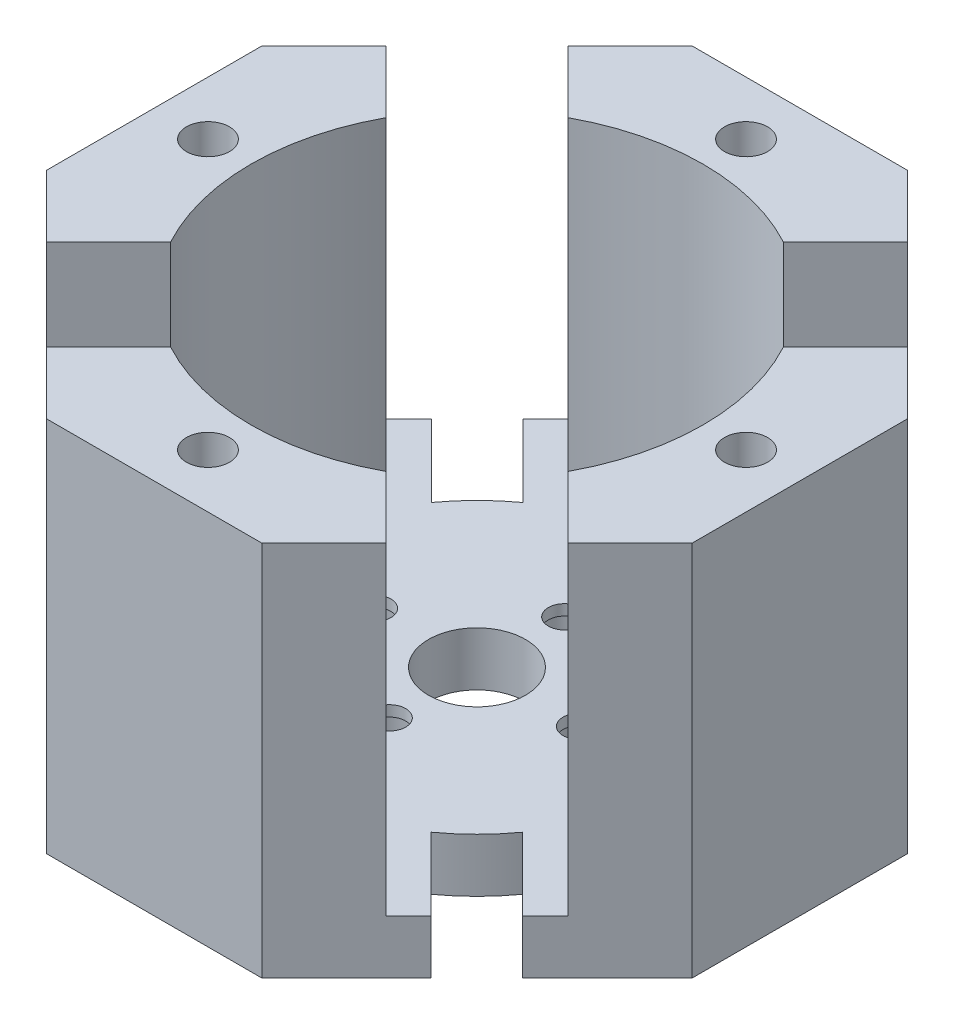
SolidWorks part; units mm, degrees
ref_plane "Front Plane" through (0, 0, 0) normal (0, 0, 1) x (1, 0, 0)
ref_plane "Top Plane" through (0, 0, 0) normal (0, 1, 0) x (1, 0, 0)
ref_plane "Right Plane" through (0, 0, 0) normal (1, 0, 0) x (0, 0, -1)
sketch "Sketch1" plane through (0, 0, 0) normal (0, 1, 0) x (1, 0, 0)
  line L1 (-30, -30) -> (30, -30)
  line L2 (-30, -30) -> (-30, 30)
  line L3 (-30, 30) -> (30, 30)
  line L4 (30, -30) -> (30, 30)
  line L5 (-30, -30) -> (30, 30) construction
  line L6 (-30, 30) -> (30, -30) construction
  point P0 (0, 0)
  dimension "D1" = 60
  dimension "D2" = 60
extrude "Boss-Extrude1" add sketch "Sketch1" along normal blind 5
sketch "Sketch2" plane through (0, 5, 0) normal (0, 1, 0) x (1, 0, 0)
  line L3 (0, 30) -> (0, -30) construction
  line L4 (30, 30) -> (-30, 30) construction
  line L5 (-30, -30) -> (30, -30) construction
  line L6 (-30, 30) -> (30, -30) construction
  circle A0 centre (-16.25, 0) radius 2
  circle A1 centre (16.25, 0) radius 2
  circle A2 centre (0, -16.25) radius 2
  circle A3 centre (0, 16.25) radius 2
  dimension "D1" = 4
  dimension "D2" = 16.25
extrude "Cut-Extrude2" cut sketch "Sketch2" against normal through all
sketch "Sketch7" plane through (0, 5, 0) normal (0, 1, 0) x (1, 0, 0)
  line L1 (-30, 30) -> (-30, -30) construction
  line L3 (30, 30) -> (-30, 30) construction
  line L5 (0, 30) -> (0, -30) construction
  line L6 (-30, -30) -> (30, -30) construction
  line L7 (-30, 0) -> (30, 0) construction
  line L8 (30, -30) -> (30, 30) construction
  line L18 (0, 0) -> (-25, 0) construction
  line L19 (-30, 30) -> (-30, 10)
  line L21 (-30, 30) -> (-10, 30)
  line L23 (-30, 10) -> (-10, 30)
  line L24 (30, 30) -> (30, 10)
  line L25 (30, 30) -> (10, 30)
  line L26 (30, 10) -> (10, 30)
  line L27 (30, -30) -> (10, -30)
  line L28 (30, -10) -> (10, -30)
  line L29 (30, -30) -> (30, -10)
  line L30 (-30, -30) -> (-30, -10)
  line L31 (-30, -30) -> (-10, -30)
  line L32 (-30, -10) -> (-10, -30)
  circle A1 centre (-25, 0) radius 2
  circle A2 centre (0, 25) radius 2
  circle A3 centre (25, 0) radius 2
  circle A4 centre (0, -25) radius 2
  point P25 (0, 0)
  dimension "D1" = 25
  dimension "D2" = 4
  dimension "D3" = 4
  dimension "D4" = 20
  dimension "D5" = 20
sketch "Sketch8" plane through (0, 5, 0) normal (0, 1, 0) x (1, 0, 0)
  circle A0 centre (0, 0) radius 4.5
  dimension "D1" = 9
extrude "Cut-Extrude4" cut sketch "Sketch8" against normal through all
ref_plane "Plane1" through (0, 5, 0) normal (0, 1, 0) x (1, 0, 0)
sketch "Sketch31" plane through (0, 5, 0) normal (0, 1, 0) x (1, 0, 0)
  circle A0 centre (0, 9.5) radius 1.5
  circle A1 centre (0, 16.25) radius 2 construction
  dimension "D1" = 6.75
  dimension "D2" = 3
extrude "Cut-Extrude20" cut sketch "Sketch31" against normal blind 10
sketch "Sketch33" plane through (0, 0, 0) normal (0, -1, 0) x (1, 0, 0)
  circle A0 centre (0, -9.5) radius 2.5
  dimension "D1" = 5
extrude "Cut-Extrude21" cut sketch "Sketch33" against normal blind 3
mirror "Mirror17" about plane through (0, 0, 0) normal (0, 0, 1) of "Cut-Extrude21", "Cut-Extrude20"
sketch "Sketch35" plane through (0, 0, 0) normal (0, -1, 0) x (1, 0, 0)
  line L0 (-3.8293, -6.5981) -> (-3.8293, -19.1464)
  line L1 (-3.8293, -19.1464) -> (3.4758, -19.1464)
  line L2 (3.4758, -19.1464) -> (3.4758, -6.5981)
  line L3 (3.4758, -6.5981) -> (6.7454, -3.3285)
  line L4 (6.7454, -3.3285) -> (18.8518, -3.3285)
  line L5 (18.8518, -3.3285) -> (18.8518, 3.6525)
  line L6 (18.8518, 3.6525) -> (6.7454, 3.6525)
  line L7 (6.7454, 3.6525) -> (3.8735, 6.5245)
  line L8 (3.8735, 6.5245) -> (3.8735, 19.3231)
  line L9 (3.8735, 19.3231) -> (-3.2402, 19.3231)
  line L10 (-3.2402, 19.3231) -> (-3.2402, 7.2462)
  line L13 (-19.6766, 3.6525) -> (-19.6766, -3.3285)
  line L14 (-19.6766, -3.3285) -> (-6.3625, -3.3285)
  line L15 (-6.3625, -3.3285) -> (-3.8293, -6.5981)
  line L16 (-19.6766, 3.6525) -> (-6.3625, 3.6525)
  line L17 (-6.3625, 3.6525) -> (-3.2402, 7.2462)
  circle A0 centre (0, 0) radius 4.5
  circle A1 centre (-16.25, 0) radius 2
  circle A2 centre (0, 16.25) radius 2
  circle A3 centre (16.25, 0) radius 2
  circle A4 centre (0, -16.25) radius 2
  dimension "D1" = 4
extrude "Boss-Extrude11" add sketch "Sketch35" against normal blind 5
sketch "Sketch37" plane through (0, 0, 0) normal (0, -1, 0) x (1, 0, 0)
  line L0 (0, 0) -> (0, 8.13) construction
  line L1 (0, 0) -> (9.5, 0) construction
  line L2 (0, 0) -> (0, -7.0105) construction
  line L3 (0, 0) -> (-8.012, 0) construction
  circle A0 centre (0, 8.13) radius 1.5
  circle A2 centre (9.5, 0) radius 1.5
  circle A4 centre (-9.5, 0) radius 1.5
  circle A5 centre (0, -8.13) radius 1.5
  dimension "D3" = 3
  dimension "D5" = 3
  dimension "D1" = 8.13
  dimension "D2" = 9.5
extrude "Cut-Extrude22" cut sketch "Sketch37" against normal blind 5
sketch "Sketch38" plane through (0, 0, 0) normal (0, -1, 0) x (1, 0, 0)
  circle A0 centre (0, 8.13) radius 2.55
  circle A1 centre (9.5, 0) radius 2.55
  circle A2 centre (0, -8.13) radius 2.55
  circle A3 centre (-9.5, 0) radius 2.55
  dimension "D1" = 5.1
  dimension "D2" = 5.1
  dimension "D3" = 5.1
  dimension "D4" = 5.1
extrude "Cut-Extrude23" cut sketch "Sketch38" against normal blind 4
extrude "Cut-Extrude24" cut sketch "Sketch7" against normal blind 10
sketch "Sketch39" plane through (0, 5, 0) normal (0, 1, 0) x (1, 0, 0)
  line L2 (-10, 30) -> (10, 30)
  line L3 (-10, 18.4662) -> (-15.7669, 24.2331)
  line L4 (-30, 10) -> (-10, 30) construction
  line L5 (10, 18.4662) -> (15.7669, 24.2331)
  line L6 (10, 30) -> (30, 10) construction
  line L7 (10, 30) -> (15.7669, 24.2331)
  line L8 (-10, 30) -> (-15.7669, 24.2331)
  line L9 (30, 10) -> (30, -10)
  line L10 (30, -10) -> (24.2331, -15.7669)
  line L11 (18.4662, -10) -> (24.2331, -15.7669)
  line L12 (18.4662, 10) -> (24.2331, 15.7669)
  line L13 (30, 10) -> (24.2331, 15.7669)
  line L14 (10, -30) -> (-10, -30)
  line L15 (-10, -30) -> (-15.7669, -24.2331)
  line L16 (-10, -18.4662) -> (-15.7669, -24.2331)
  line L17 (10, -18.4662) -> (15.7669, -24.2331)
  line L18 (10, -30) -> (15.7669, -24.2331)
  line L19 (-30, -10) -> (-30, 10)
  line L20 (-30, 10) -> (-24.2331, 15.7669)
  line L21 (-18.4662, 10) -> (-24.2331, 15.7669)
  line L22 (-18.4662, -10) -> (-24.2331, -15.7669)
  line L23 (-30, -10) -> (-24.2331, -15.7669)
  arc A0 (10, 18.4662) -> (-10, 18.4662) centre (0, 0) ccw
  arc A1 (18.4662, -10) -> (18.4662, 10) centre (0, 0) ccw
  arc A2 (-10, -18.4662) -> (10, -18.4662) centre (0, 0) ccw
  arc A3 (-18.4662, 10) -> (-18.4662, -10) centre (0, 0) ccw
  point P35 (0, 0)
  dimension "D1" = 4
extrude "Boss-Extrude12" add sketch "Sketch39" along normal blind 30
sketch "Sketch40" plane through (0, 35, 0) normal (0, 1, 0) x (1, 0, 0)
  line L0 (0, 0) -> (-25, 0) construction
  circle A0 centre (-25, 0) radius 2
  dimension "D2" = 4
  dimension "D1" = 25
extrude "Cut-Extrude25" cut sketch "Sketch40" against normal blind 6
ref_plane "Plane2" through (0, 0, 0) normal (0.7071, 0, -0.7071) x (-0.7071, 0, -0.7071)
mirror "Mirror19" about plane through (0, 0, 0) normal (1, 0, 0) of "Cut-Extrude25"
mirror "Mirror20" about plane through (0, 0, 0) normal (0.7071, 0, -0.7071) of "Cut-Extrude25", "Mirror19"
sketch "Sketch42" plane through (0, 5, 0) normal (0, 1, 0) x (1, 0, 0)
  line L0 (-20, 20) -> (-24.2331, 15.7669) construction
  line L1 (-24.2331, 15.7669) -> (-15.7669, 24.2331) construction
  line L2 (-24.2331, 15.7669) -> (-15.7669, 24.2331) construction
  line L3 (-22.1165, 17.8835) -> (-15.3838, 11.1507)
  line L5 (-11.1396, 15.3918) -> (-17.8739, 22.1261)
  line L6 (-17.8739, 22.1261) -> (-22.1165, 17.8835)
  line L7 (22.1261, 17.8739) -> (17.8835, 22.1165)
  line L8 (17.8835, 22.1165) -> (11.1507, 15.3838)
  line L10 (15.3918, 11.1396) -> (22.1261, 17.8739)
  line L11 (17.8739, -22.1261) -> (22.1165, -17.8835)
  line L12 (22.1165, -17.8835) -> (15.3838, -11.1507)
  line L14 (11.1396, -15.3918) -> (17.8739, -22.1261)
  line L15 (-22.1261, -17.8739) -> (-17.8835, -22.1165)
  line L16 (-17.8835, -22.1165) -> (-11.1507, -15.3838)
  line L18 (-15.3918, -11.1396) -> (-22.1261, -17.8739)
  arc A0 (-15.3918, -11.1396) -> (-11.1507, -15.3838) centre (0, 0) ccw
  arc A1 (-11.1396, 15.3918) -> (-15.3838, 11.1507) centre (0, 0) ccw
  arc A2 (15.3918, 11.1396) -> (11.1507, 15.3838) centre (0, 0) ccw
  arc A3 (11.1396, -15.3918) -> (15.3838, -11.1507) centre (0, 0) ccw
  point P26 (0, 0)
  dimension "D4" = 38
  dimension "D3" = 4
extrude "Cut-Extrude27" cut sketch "Sketch42" against normal blind 10
